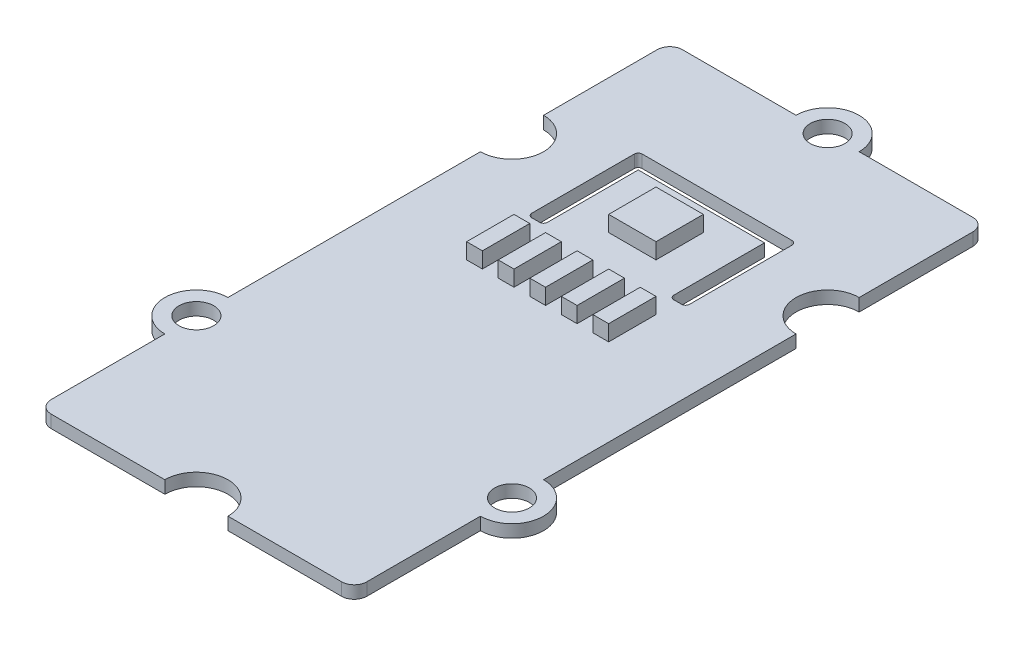
SolidWorks part; units mm, degrees
ref_plane "Front Plane" through (0, 0, 0) normal (0, 0, 1) x (1, 0, 0)
ref_plane "Top Plane" through (0, 0, 0) normal (0, 1, 0) x (1, 0, 0)
ref_plane "Right Plane" through (0, 0, 0) normal (1, 0, 0) x (0, 0, -1)
sketch "Sketch1" plane through (0, 0, 0) normal (0, 1, 0) x (1, 0, 0)
  line L0 (10, 0) -> (10, 40) construction
  line L1 (0.8, 0) -> (8, 0)
  line L2 (0, 0.8) -> (0, 8)
  line L3 (0.8, 40) -> (8, 40)
  line L4 (20, 0.8) -> (20, 8)
  line L5 (12, 40) -> (19.2, 40)
  line L6 (0, 32) -> (0, 39.2)
  line L7 (20, 32) -> (20, 39.2)
  line L8 (0, 12) -> (0, 28)
  line L9 (20, 12) -> (20, 28)
  line L10 (12, 0) -> (19.2, 0)
  arc A0 (0.8, 0) -> (0, 0.8) centre (0.8, 0.8) cw
  arc A1 (19.2, 0) -> (20, 0.8) centre (19.2, 0.8) ccw
  arc A2 (19.2, 40) -> (20, 39.2) centre (19.2, 39.2) cw
  arc A3 (0, 39.2) -> (0.8, 40) centre (0.8, 39.2) cw
  arc A4 (12, 40) -> (8, 40) centre (10, 40) ccw
  circle A5 centre (10, 40) radius 1.1
  arc A6 (0, 28) -> (0, 32) centre (0, 30) ccw
  arc A7 (20, 32) -> (20, 28) centre (20, 30) ccw
  arc A8 (0, 12) -> (0, 8) centre (0, 10) ccw
  arc A9 (20, 8) -> (20, 12) centre (20, 10) ccw
  arc A10 (12, 0) -> (8, 0) centre (10, 0) ccw
  circle A11 centre (0, 10) radius 1.1
  circle A12 centre (20, 10) radius 1.1
  point P7 (0, 0)
  point P10 (20, 0)
  point P13 (20, 40)
  dimension "D3" = 0.8
  dimension "D4" = 2
  dimension "D5" = 2.2
  dimension "D1" = 20
  dimension "D2" = 40
  dimension "D6" = 10
  dimension "D7" = 30
  dimension "D8" = 30
extrude "Board" add sketch "Sketch1" along normal blind 0.8
sketch "Sketch2" plane through (0, 0.8, 0) normal (0, 1, 0) x (1, 0, 0)
  line L0 (14.25, 26) -> (14.75, 26)
  line L1 (5.25, 33) -> (14.75, 33)
  line L2 (5, 32.75) -> (5, 26.25)
  line L3 (5.25, 26) -> (5.75, 26)
  line L4 (15, 32.75) -> (15, 26.25)
  line L6 (6, 26.25) -> (6, 32)
  line L7 (6, 32) -> (14, 32)
  line L8 (14, 26.25) -> (14, 32)
  line L9 (8, 40) -> (0.8, 40) construction
  arc A0 (12, 40) -> (8, 40) centre (10, 40) ccw construction
  arc A1 (5, 26.25) -> (5.25, 26) centre (5.25, 26.25) ccw
  arc A2 (5.75, 26) -> (6, 26.25) centre (5.75, 26.25) ccw
  arc A3 (14.75, 26) -> (15, 26.25) centre (14.75, 26.25) ccw
  arc A4 (14.25, 26) -> (14, 26.25) centre (14.25, 26.25) cw
  arc A5 (14.75, 33) -> (15, 32.75) centre (14.75, 32.75) cw
  arc A6 (5.25, 33) -> (5, 32.75) centre (5.25, 32.75) ccw
  point P8 (10, 32)
  point P9 (10, 33)
  point P14 (10, 42)
  point P19 (5, 26)
  point P22 (6, 26)
  point P25 (15, 26)
  point P30 (15, 33)
  point P33 (5, 33)
  dimension "D6" = 0.25
  dimension "D1" = 1
  dimension "D2" = 1
  dimension "D3" = 7
  dimension "D4" = 10
  dimension "D5" = 7
extrude "U-cut" cut sketch "Sketch2" against normal through all both and the other way through all
sketch "Sketch3" plane through (0, 0.8, 0) normal (0, 1, 0) x (1, 0, 0)
  line L0 (14, 32) -> (6, 32) construction
  line L1 (8.5, 30.625) -> (11.5, 30.625)
  line L2 (8.5, 30.625) -> (8.5, 27.625)
  line L3 (8.5, 27.625) -> (11.5, 27.625)
  line L4 (11.5, 30.625) -> (11.5, 27.625)
  line L5 (9.5, 24.625) -> (10.5, 24.625)
  line L6 (9.5, 24.625) -> (9.5, 21.625)
  line L7 (9.5, 21.625) -> (10.5, 21.625)
  line L8 (10.5, 24.625) -> (10.5, 21.625)
  line L9 (6, 32) -> (6, 26.25) construction
  line L10 (11.5, 24.625) -> (11.5, 21.625)
  line L11 (11.5, 24.625) -> (12.5, 24.625)
  line L12 (12.5, 24.625) -> (12.5, 21.625)
  line L13 (11.5, 21.625) -> (12.5, 21.625)
  line L14 (13.5, 24.625) -> (13.5, 21.625)
  line L15 (13.5, 24.625) -> (14.5, 24.625)
  line L16 (14.5, 24.625) -> (14.5, 21.625)
  line L17 (13.5, 21.625) -> (14.5, 21.625)
  line L18 (9.5, 24.625) -> (9.5, 21.625)
  line L19 (9.5, 24.625) -> (10.5, 24.625)
  line L20 (10.5, 24.625) -> (10.5, 21.625)
  line L21 (9.5, 21.625) -> (10.5, 21.625)
  line L22 (11.5, 24.625) -> (11.5, 21.625)
  line L23 (11.5, 24.625) -> (12.5, 24.625)
  line L24 (12.5, 24.625) -> (12.5, 21.625)
  line L25 (11.5, 21.625) -> (12.5, 21.625)
  line L26 (7.5, 24.625) -> (7.5, 21.625)
  line L27 (7.5, 24.625) -> (8.5, 24.625)
  line L28 (8.5, 24.625) -> (8.5, 21.625)
  line L29 (7.5, 21.625) -> (8.5, 21.625)
  line L30 (9.5, 24.625) -> (9.5, 21.625)
  line L31 (9.5, 24.625) -> (10.5, 24.625)
  line L32 (10.5, 24.625) -> (10.5, 21.625)
  line L33 (9.5, 21.625) -> (10.5, 21.625)
  line L34 (7.5, 24.625) -> (7.5, 21.625)
  line L35 (7.5, 24.625) -> (8.5, 24.625)
  line L36 (8.5, 24.625) -> (8.5, 21.625)
  line L37 (7.5, 21.625) -> (8.5, 21.625)
  line L38 (5.5, 24.625) -> (5.5, 21.625)
  line L39 (5.5, 24.625) -> (6.5, 24.625)
  line L40 (6.5, 24.625) -> (6.5, 21.625)
  line L41 (5.5, 21.625) -> (6.5, 21.625)
  line L42 (9.5, 24.625) -> (11.5, 24.625) construction
  line L43 (9.5, 24.625) -> (7.5, 24.625) construction
  point P10 (10, 32)
  point P11 (10, 30.625)
  point P12 (10, 24.625)
  point P13 (8.5, 29.125)
  point P16 (6, 29.125)
  dimension "D1" = 3
  dimension "D2" = 3
  dimension "D3" = 1
  dimension "D4" = 3
  dimension "D5" = 3
  dimension "D8" = 2
  dimension "D9" = 2
  dimension "D6" = 3
  dimension "D7" = 3
extrude "SMDs" add sketch "Sketch3" along normal blind 1 contours L38 L41 L40 L39 | L26 L29 L28 L27 | L8 L5 L6 L7 | L10 L13 L12 L11 | L14 L17 L16 L15 | L4 L1 L2 L3
